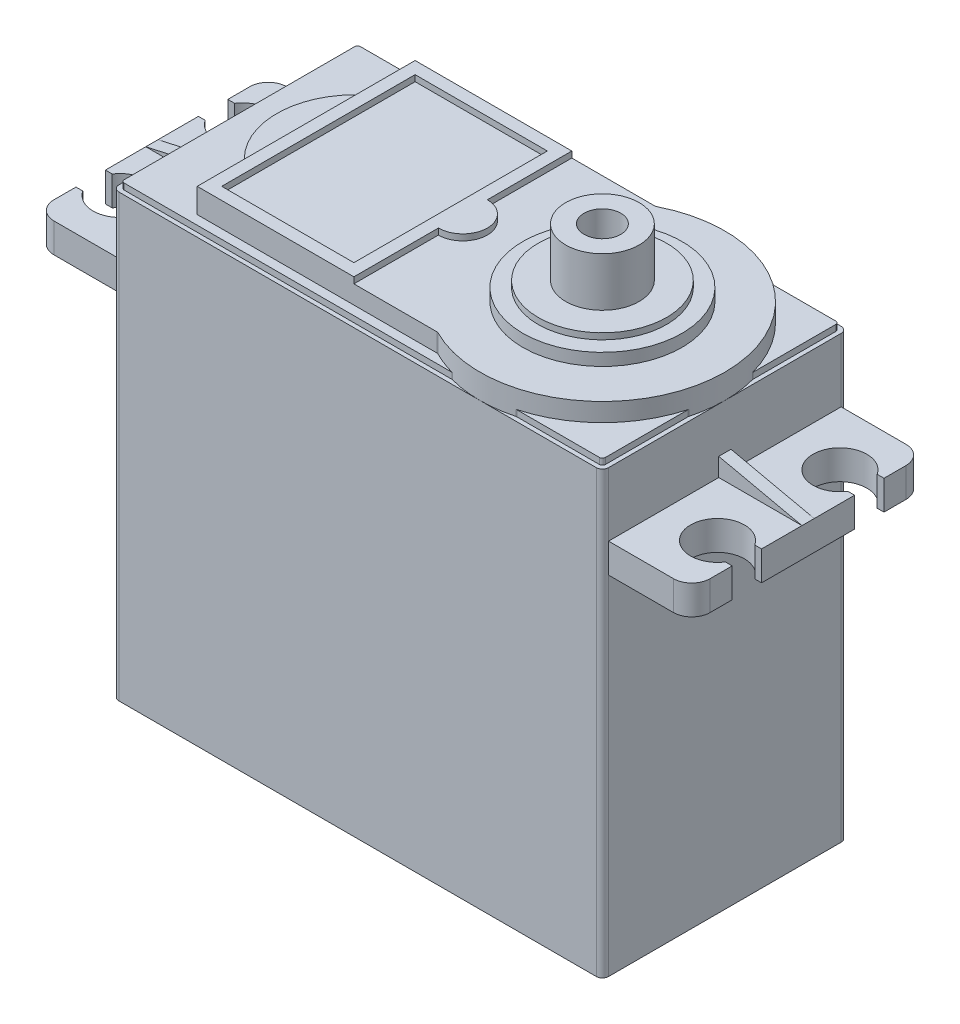
SolidWorks part; units mm, degrees
ref_plane "Front Plane" through (0, 0, 0) normal (0, 0, 1) x (1, 0, 0)
ref_plane "Top Plane" through (0, 0, 0) normal (0, 1, 0) x (1, 0, 0)
ref_plane "Right Plane" through (0, 0, 0) normal (1, 0, 0) x (0, 0, -1)
sketch "Sketch1" plane through (0, 0, 0) normal (0, 1, 0) x (1, 0, 0)
  line L1 (-20, 10) -> (20, 10)
  line L2 (-20, 10) -> (-20, -10)
  line L3 (-20, -10) -> (20, -10)
  line L4 (20, 10) -> (20, -10)
  line L5 (-20, 10) -> (20, -10) construction
  line L6 (-20, -10) -> (20, 10) construction
  point P0 (0, 0)
  dimension "D1" = 20
  dimension "D2" = 40
extrude "Boss-Extrude1" add sketch "Sketch1" along normal blind 38 contours L2 L3 L4 L1
sketch "Sketch2" plane through (0, 38, 0) normal (0, 1, 0) x (1, 0, 0)
  line L0 (-20, 0) -> (20, 0) construction
  line L1 (-14.2, 8.9) -> (5.4404, 8.9)
  line L2 (-14.2, 8.9) -> (-14.2, -8.9)
  line L3 (-14.2, -8.9) -> (5.4404, -8.9)
  line L4 (5.4404, 8.9) -> (5.4404, -8.9)
  line L5 (-14.2, 8.9) -> (5.4404, -8.9) construction
  line L6 (-14.2, -8.9) -> (5.4404, 8.9) construction
  line L7 (-20, 10) -> (-20, -10) construction
  line L8 (20, 10) -> (20, -10) construction
  line L9 (-20, 10) -> (20, 10) construction
  line L10 (-10.1917, 0) -> (-16.6, 0) construction
  circle A0 centre (-10.1917, 0) radius 6.4083
  circle A1 centre (10, 0) radius 10
  point P0 (-4.3798, 0)
  point P15 (-14.2, 5)
  dimension "D3" = 5
  dimension "D1" = 17.8
  dimension "D2" = 5.8
  dimension "D4" = 3.4
extrude "Boss-Extrude2" add sketch "Sketch2" along normal blind 2 contours L2 A0 | A1 L1 L2 A0 L3 | L2 A0 | A1 L4 | L4 A1
sketch "Sketch3" plane through (0, 38, 0) normal (0, 1, 0) x (1, 0, 0)
  line L0 (-20, 10) -> (-20, -10) construction
  line L1 (-20, -10) -> (10, -10) construction
  line L2 (10, -10) -> (20, -10) construction
  line L3 (20, 0) -> (20, -10) construction
  line L4 (20, 10) -> (20, 0) construction
  line L5 (-20, 10) -> (10, 10) construction
  line L6 (10, 10) -> (20, 10) construction
  line L7 (-20, 10) -> (-20, -10) construction
  line L8 (-20, -10) -> (10, -10) construction
  line L9 (10, -10) -> (20, -10) construction
  line L10 (20, 0) -> (20, -10) construction
  line L11 (20, 10) -> (20, 0) construction
  line L12 (-20, 10) -> (10, 10) construction
  line L13 (10, 10) -> (20, 10) construction
  line L14 (-19.65, 9.65) -> (10, 9.65)
  line L15 (10, 9.65) -> (19.65, 9.65)
  line L16 (19.65, 9.65) -> (19.65, 0)
  line L17 (19.65, 0) -> (19.65, -9.65)
  line L18 (10, -9.65) -> (19.65, -9.65)
  line L19 (-19.65, -9.65) -> (10, -9.65)
  line L20 (-19.65, 9.65) -> (-19.65, -9.65)
  dimension "D1" = 0.35
extrude "Boss-Extrude3" add sketch "Sketch3" along normal blind 0.5
sketch "Sketch6" plane through (0, 40, 0) normal (0, 1, 0) x (1, 0, 0)
  line L0 (-14.2, -8.9) -> (5.4404, -8.9) construction
  line L1 (-14.2, 8.9) -> (-1.4, 8.9)
  line L2 (-14.2, 8.9) -> (-14.2, -8.9)
  line L3 (-14.2, -8.9) -> (-1.4, -8.9)
  line L4 (-1.4, 8.9) -> (-1.4, -8.9)
  line L5 (-2.4, 7.9) -> (-2.4, -7.9)
  line L6 (-13.2, -7.9) -> (-2.4, -7.9)
  line L7 (-13.2, 7.9) -> (-13.2, -7.9)
  line L8 (-13.2, 7.9) -> (-2.4, 7.9)
  dimension "D1" = 12.8
  dimension "D2" = 1
extrude "Boss-Extrude4" add sketch "Sketch6" along normal blind 0.5
sketch "Sketch7" plane through (0, 40, 0) normal (0, 1, 0) x (1, 0, 0)
  line L0 (0, 0) -> (-20, 0) construction
  line L1 (-20, 10) -> (-20, -10) construction
  line L2 (-1.4, -8.9) -> (-1.4, 8.9) construction
  line L3 (-1.4, -8.9) -> (-1.4, 8.9) construction
  line L4 (-1.4, 2) -> (-1.4, -2)
  circle A0 centre (-1.4, 0) radius 2
  line M2 (-1.4, 8.9) -> (-1.4, -8.9)
  dimension "D1" = 4
extrude "Boss-Extrude5" add sketch "Sketch7" along normal blind 0.5 contours A0 M2
sketch "Sketch8" plane through (0, 40, 0) normal (0, 1, 0) x (1, 0, 0)
  circle A0 centre (10, 0) radius 6.5
  dimension "D1" = 13
extrude "Boss-Extrude6" add sketch "Sketch8" along normal blind 1 contours A0
sketch "Sketch9" plane through (0, 41, 0) normal (0, 1, 0) x (1, 0, 0)
  circle A0 centre (10, 0) radius 5.25
  dimension "D1" = 10.5
extrude "Boss-Extrude7" add sketch "Sketch9" along normal blind 0.5
sketch "Sketch10" plane through (0, 41.5, 0) normal (0, 1, 0) x (1, 0, 0)
  circle A0 centre (10, 0) radius 3
  dimension "D1" = 6
extrude "Boss-Extrude8" add sketch "Sketch10" along normal blind 4
sketch "Sketch11" plane through (0, 45.5, 0) normal (0, 1, 0) x (1, 0, 0)
  circle A0 centre (10, 0) radius 1.5
  dimension "D1" = 3
extrude "Cut-Extrude1" cut sketch "Sketch11" against normal blind 10
chamfer "Chamfer1" distance 2 angle 45 4 edges at (-20, 0, 0) (0, 0, -10) (20, 0, 0) (0, 0, 10)
sketch "Sketch12" plane through (0, 0, 0) normal (0, -1, 0) x (1, 0, 0)
  line L0 (0, 0) -> (20, 0) construction
  line L1 (20, 10) -> (20, -10) construction
  line L2 (20, 0) -> (0, 0) construction
  line L3 (0, 0) -> (0, 10) construction
  line L4 (-20, 10) -> (20, 10) construction
  line L5 (18, 8) -> (20, 10) construction
  circle A0 centre (19, 9) radius 2
  circle A1 centre (-19, 9) radius 2
  circle A2 centre (19, -9) radius 2
  circle A3 centre (-19, -9) radius 2
  dimension "D1" = 4
extrude "Cut-Extrude2" cut sketch "Sketch12" against normal up to vertex (2 mm away)
ref_plane "Plane1" through (0, 32.8, 0) normal (0, 1, 0) x (1, 0, 0)
fillet "Fillet1" radius 0.5 4 edges at (20, 20, -10) (20, 20, 10) (-20, 20, 10) (-20, 20, -10)
fillet "Fillet2" radius 0.25 12 edges at (5.4404, 39.25, 8.9) (12.6225, 38.25, -9.65) (7.3775, 38.25, -9.65) (5.4404, 39.25, -8.9) (-19.65, 38.25, -9.65) (-19.65, 38.25, 9.65) (19.65, 38.25, -9.65) (19.65, 38.25, 2.6225) (19.65, 38.25, -2.6225) (19.65, 38.25, 9.65) (12.6225, 38.25, 9.65) (7.3775, 38.25, 9.65)
sketch "Sketch13" plane through (0, 32.8, 0) normal (0, 1, 0) x (1, 0, 0)
  line L0 (-20, 9.5) -> (-20, -9.5) construction
  line L1 (-20, 9.5) -> (-26.8, 9.5)
  line L2 (-20, 9.5) -> (-20, -9.5)
  line L3 (-20, -9.5) -> (-26.8, -9.5)
  line L4 (-26.8, 9.5) -> (-26.8, -9.5)
  line L5 (0, 0) -> (0, -14.3124) construction
  line L6 (0, 0) -> (-34.2584, 0) construction
  line L7 (-24.4, 5) -> (-38.9891, 5) construction
  line L8 (-29.2, 3.8) -> (-24.4, 3.8)
  line L9 (-29.2, 3.8) -> (-29.2, 6.2)
  line L10 (-29.2, 6.2) -> (-24.4, 6.2)
  line L11 (-24.4, 3.8) -> (-24.4, 6.2)
  line L12 (-29.2, 3.8) -> (-24.4, 6.2) construction
  line L13 (-29.2, 6.2) -> (-24.4, 3.8) construction
  line L14 (-29.2, -6.2) -> (-24.4, -6.2)
  line L15 (-24.4, -3.8) -> (-24.4, -6.2)
  line L16 (-29.2, -3.8) -> (-24.4, -3.8)
  line L17 (-29.2, -3.8) -> (-29.2, -6.2)
  line L18 (29.2, 6.2) -> (24.4, 6.2)
  line L19 (24.4, 3.8) -> (24.4, 6.2)
  line L20 (29.2, 3.8) -> (24.4, 3.8)
  line L21 (29.2, 3.8) -> (29.2, 6.2)
  line L22 (24.4, -3.8) -> (24.4, -6.2)
  line L23 (29.2, -3.8) -> (29.2, -6.2)
  line L24 (29.2, -6.2) -> (24.4, -6.2)
  line L25 (29.2, -3.8) -> (24.4, -3.8)
  line L26 (20, -9.5) -> (26.8, -9.5)
  line L27 (26.8, 9.5) -> (26.8, -9.5)
  line L28 (20, 9.5) -> (26.8, 9.5)
  line L29 (20, 9.5) -> (20, -9.5)
  arc A0 (-19.5, 10) -> (-20, 9.5) centre (-19.5, 9.5) ccw construction
  circle A1 centre (-24.4, 5) radius 2.2
  circle A2 centre (-24.4, -5) radius 2.2
  circle A3 centre (24.4, 5) radius 2.2
  circle A4 centre (24.4, -5) radius 2.2
  point P15 (-26.8, 5)
  point P21 (-24.4, 5)
  dimension "D4" = 4.4
  dimension "D1" = 6.8
  dimension "D2" = 19
  dimension "D3" = 5
  dimension "D5" = 2.4
  dimension "D6" = 2.4
extrude "Boss-Extrude9" add sketch "Sketch13" against normal blind 2.4 contours L16 A2 L14 L4 L3 L2 L1 L10 A1 L8 | A4 L25 L27 L20 A3 L18 L28 L29 L26 L24
sketch "Sketch14" plane through (0, 0, 0) normal (0, 0, 1) x (1, 0, 0)
  line L0 (-26.8, 32.8) -> (-20, 32.8)
  line L1 (10.6244, 32.8) -> (-10.6244, 32.8) construction
  line L2 (-20, 32.8) -> (-26.8, 32.8) construction
  line L3 (-20, 32.8) -> (-20, 34.3)
  line L4 (-20, 32.8) -> (-20, 38) construction
  line L5 (-20, 34.3) -> (-26.8, 32.8)
  line L6 (0, 46.3059) -> (0, -3.398) construction
  line L7 (20, 32.8) -> (20, 34.3)
  line L8 (26.8, 32.8) -> (20, 32.8)
  line L9 (20, 34.3) -> (26.8, 32.8)
  dimension "D1" = 1.5
extrude "Boss-Extrude10" add sketch "Sketch14" along normal blind 0.5 and the other way blind 0.5
fillet "Fillet3" radius 1.5 4 edges at (26.8, 31.6, -9.5) (26.8, 31.6, 9.5) (-26.8, 31.6, -9.5) (-26.8, 31.6, 9.5)
